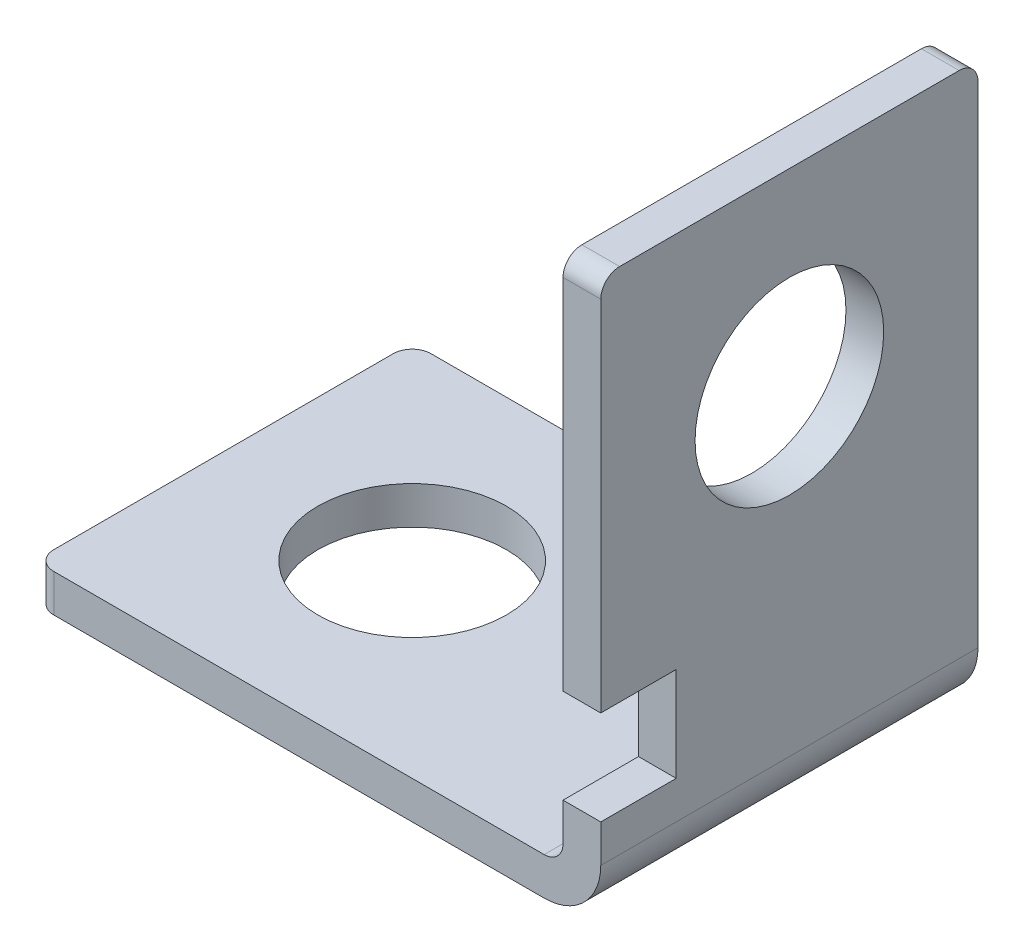
SolidWorks part; units mm, degrees
material "6061 Alloy"
ref_plane "Front Plane" through (0, 0, 0) normal (0, 0, 1) x (1, 0, 0)
ref_plane "Top Plane" through (0, 0, 0) normal (0, 1, 0) x (1, 0, 0)
ref_plane "Right Plane" through (0, 0, 0) normal (1, 0, 0) x (0, 0, -1)
sketch "Sketch2" plane through (0, 0, 0) normal (0, 0, 1) x (1, 0, 0)
  line L0 (0, 0) -> (27, 0)
  line L1 (30, 3) -> (30, 30)
  line L2 (0, 0) -> (0, 2)
  line L3 (0, 2) -> (27, 2)
  line L4 (30, 30) -> (28, 30)
  line L5 (28, 30) -> (28, 3)
  arc A0 (27, 0) -> (30, 3) centre (27, 3) ccw
  arc A1 (28, 3) -> (27, 2) centre (27, 3) cw
  point P6 (30, 0)
  point P9 (27.5745, 2)
  point P13 (25, 2)
  point P14 (25, 2)
  point P15 (0, 0)
  point P16 (0, 0)
  dimension "D3" = 3
  dimension "D5" = 2
  dimension "D1" = 30
  dimension "D2" = 30
  dimension "D4" = 2
extrude "Boss-Extrude1" add sketch "Sketch2" along normal blind 20
fillet "Fillet1" radius 1 4 edges at (0, 1, 20) (0, 1, 0) (29, 30, 0) (29, 30, 20)
sketch "Sketch3" plane through (28, 0, 0) normal (-1, 0, 0) x (0, 0, 1)
  line L0 (10, 30) -> (10, 20) construction
  line L1 (19, 30) -> (1, 30) construction
  line L2 (10, 20) -> (10, 10) construction
  line L3 (20, 10) -> (16, 10)
  line L4 (20, 29) -> (20, 3) construction
  line L5 (16, 10) -> (16, 5)
  line L6 (16, 5) -> (20, 5)
  line L7 (20, 5) -> (20, 10)
  circle A0 centre (10, 20) radius 5
  dimension "D5" = 10
  dimension "D1" = 5
  dimension "D2" = 4
  dimension "D3" = 20
  dimension "D4" = 10
extrude "Cut-Extrude1" cut sketch "Sketch3" against normal through all
sketch "Sketch4" plane through (0, 2, 0) normal (0, 1, 0) x (1, 0, 0)
  line L0 (0, -10) -> (10, -10) construction
  line L1 (0, -19) -> (0, -1) construction
  circle A0 centre (10, -10) radius 5
  dimension "D2" = 10
  dimension "D1" = 10
extrude "Cut-Extrude2" cut sketch "Sketch4" against normal through all
